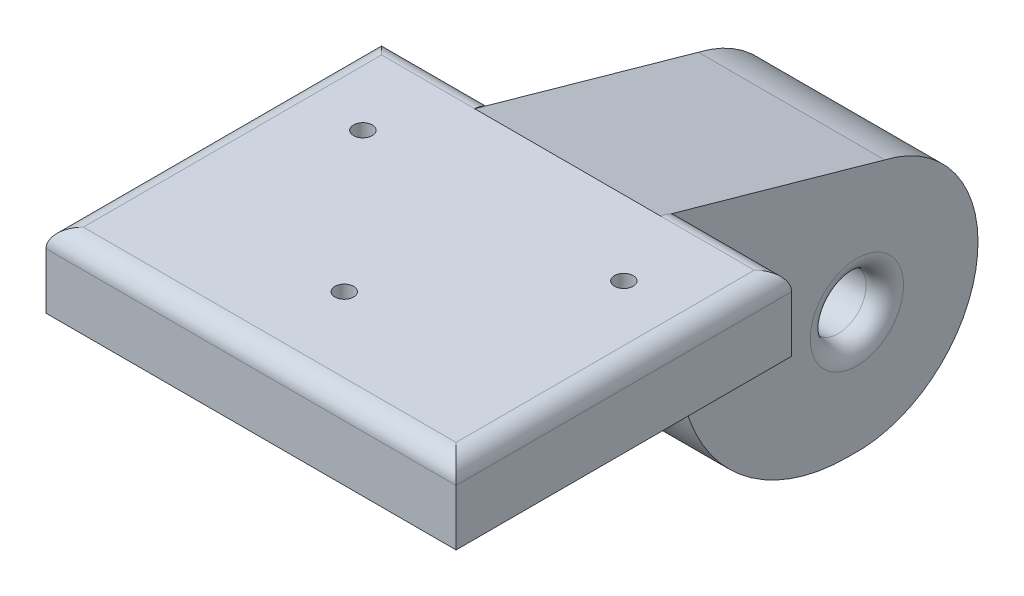
SolidWorks part; units mm, degrees
ref_plane "Front Plane" through (0, 0, 0) normal (0, 0, 1) x (1, 0, 0)
ref_plane "Top Plane" through (0, 0, 0) normal (0, 1, 0) x (1, 0, 0)
ref_plane "Right Plane" through (0, 0, 0) normal (1, 0, 0) x (0, 0, -1)
sketch "Sketch1" plane through (0, 0, 0) normal (0, 1, 0) x (1, 0, 0)
  line L1 (-8.2409, 25.3577) -> (2.7591, 25.3577)
  line L2 (-8.2409, 25.3577) -> (-8.2409, 7.3577)
  line L3 (-8.2409, 7.3577) -> (2.7591, 7.3577)
  line L4 (2.7591, 25.3577) -> (2.7591, 7.3577)
  line L5 (-8.2409, 25.3577) -> (-3.2409, 25.3577)
  line L6 (-8.2409, 25.3577) -> (-8.2409, 36.3577)
  line L7 (-8.2409, 36.3577) -> (-3.2409, 36.3577)
  line L8 (-3.2409, 25.3577) -> (-3.2409, 36.3577)
  dimension "D1" = 18
  dimension "D2" = 11
  dimension "D3" = 6
  dimension "D4" = 11
extrude "Boss-Extrude1" add sketch "Sketch1" along normal blind 4 contours L4 L1 L2 L3 | L1 L8 L7 L6
sketch "Sketch2" plane through (-3.2409, 0, 0) normal (1, 0, 0) x (0, 0, -1)
  line L0 (36.3577, 4) -> (36.3577, 0) construction
  line L1 (25.3577, 0) -> (34.5379, 0)
  line L2 (25.3577, 0) -> (25.3577, -12.1921)
  line L3 (25.3577, -12.1921) -> (34.5379, -12.1921)
  line L4 (34.5379, 0) -> (34.5379, -12.1921)
  circle A0 centre (34.8577, -5.7) radius 1.5
  arc A1 (34.5379, -12.1921) -> (36.3577, 0.6246) centre (34.8577, -5.7) ccw
  line M6 (25.3577, 0) -> (36.3577, 0)
  line M7 (36.3577, 0) -> (36.3577, 4)
  dimension "D2" = 9.5
  dimension "D1" = 5.7
extrude "Boss-Extrude2" add sketch "Sketch2" against normal blind 5 contours A0 L4 L2 L3 M6 | L4 A1 A0 M7 M6
mirror "Mirror1" about plane through (-8.2409, 4, 0) normal (1, 0, 0) of "Boss-Extrude2", "Boss-Extrude1"
sketch "Sketch3" plane through (0, 4, 0) normal (0, 1, 0) x (1, 0, 0)
  line L0 (-8.2409, 41.3577) -> (-8.2409, 7.0572) construction
  line L1 (-3.2409, 41.3577) -> (-13.2409, 41.3577) construction
  line L2 (2.7591, 25.3577) -> (2.7591, 7.3577) construction
  line L3 (-3.2409, 25.3577) -> (2.7591, 25.3577) construction
  line L4 (-19.2409, 7.3577) -> (2.7591, 7.3577) construction
  circle A0 centre (-1.2409, 20.3577) radius 0.5
  circle A1 centre (-8.2409, 12.3577) radius 0.5
  circle A2 centre (-15.2409, 20.3577) radius 0.5
  dimension "D1" = 4
  dimension "D2" = 5
  dimension "D3" = 5
extrude "Cut-Extrude1" cut sketch "Sketch3" against normal blind 5
fillet "Fillet1" radius 1 7 edges at (-0.2409, 4, -25.3577) (2.7591, 4, -16.3577) (-8.2409, 4, -7.3577) (-16.2409, 4, -25.3577) (-19.2409, 4, -16.3577) (-13.2409, -5.7, -36.3577) (-3.2409, -5.7, -36.3577)
fillet "Fillet3" radius 2 1 edges at (-8.2409, 0, -25.3577)
fillet "Fillet4" radius 9 1 edges at (-8.2409, -12.1921, -25.3577)
sketch "Sketch4" plane through (-13.2409, 0, 0) normal (-1, 0, 0) x (0, 0, 1)
  line L0 (-36.3577, 0.6246) -> (-24.3577, 4)
  line L1 (-36.3577, 4) -> (-36.3577, 0.6246) construction
  line L2 (-36.3577, 0.6246) -> (-36.3577, 4)
  line L4 (-36.3577, 4) -> (-24.3577, 4)
extrude "Cut-Extrude2" cut sketch "Sketch4" against normal blind 10
equation "\"7cmmm\"=6.5"
